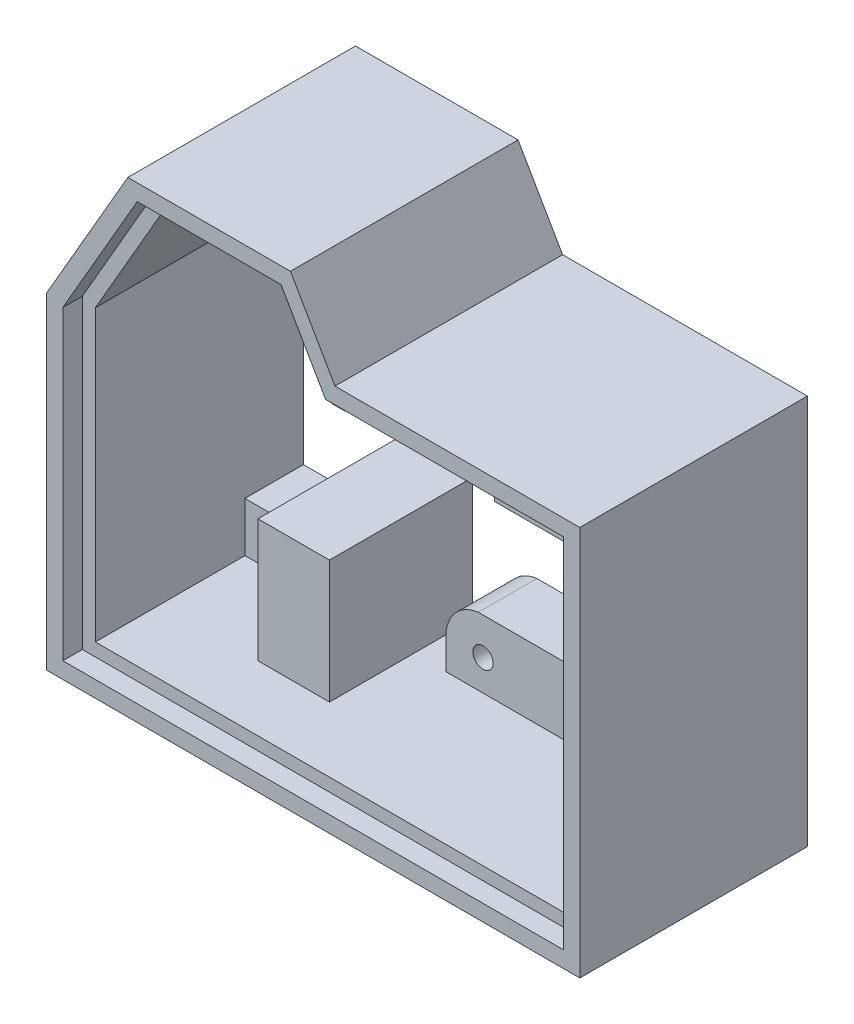
SolidWorks part; units mm, degrees
ref_plane "Front Plane" through (0, 0, 0) normal (0, 0, 1) x (1, 0, 0)
ref_plane "Top Plane" through (0, 0, 0) normal (0, 1, 0) x (1, 0, 0)
ref_plane "Right Plane" through (0, 0, 0) normal (1, 0, 0) x (0, 0, -1)
sketch "Sketch1" plane through (0, 0, 0) normal (0, 0, 1) x (1, 0, 0)
  line L1 (0, 0) -> (82, 0)
  line L2 (0, 0) -> (0, 50.2188)
  line L3 (5.6472, 60) -> (82, 60)
  line L4 (82, 0) -> (82, 60)
  line L5 (0, 50.2188) -> (50, 50.2188)
  line L6 (12.5, 71.8694) -> (12.5, 50.2188)
  line L10 (50, 50.2188) -> (37.5, 71.8694)
  line L11 (37.5, 71.8694) -> (12.5, 71.8694)
  line L12 (12.5, 71.8694) -> (0, 50.2188)
  line L13 (37.5, 28.5681) -> (43.75, 39.3934) [skipped]
  line L14 (12.5, 28.5681) -> (25, 28.5681) [skipped]
  line L15 (0, 50.2188) -> (6.25, 39.3934) [skipped]
  arc A0 (46.6506, 50.2188) -> (3.3494, 50.2188) centre (25, 50.2188) ccw construction
  dimension "D1" = 50.2188
  dimension "D4" = 21.6506
extrude "Boss-Extrude1" add sketch "Sketch1" along normal blind 35 contours L10 L11 L6 L3 | L3 L12 L5 L6 | L6 L12 L3 | L5 L10 L3 L6 | L10 L5 L2 L1 L4 L3
sketch "Sketch3" plane through (0, 0, 35) normal (0, 0, 1) x (1, 0, 0)
  line L14 (42.9094, 57.5) -> (36.0566, 69.3694)
  line L15 (36.0566, 69.3694) -> (13.9434, 69.3694)
  line L16 (13.9434, 69.3694) -> (2.5, 49.5489)
  line L17 (2.5, 49.5489) -> (2.5, 2.5)
  line L18 (2.5, 2.5) -> (79.5, 2.5)
  line L19 (79.5, 2.5) -> (79.5, 57.5)
  line L20 (79.5, 57.5) -> (42.9094, 57.5)
  line L21 (42.9094, 57.5) -> (36.0566, 69.3694)
  line L22 (36.0566, 69.3694) -> (13.9434, 69.3694)
  line L23 (13.9434, 69.3694) -> (2.5, 49.5489)
  line L24 (2.5, 49.5489) -> (2.5, 2.5)
  line L25 (2.5, 2.5) -> (79.5, 2.5)
  line L26 (79.5, 2.5) -> (79.5, 57.5)
  line L27 (79.5, 57.5) -> (42.9094, 57.5)
  point P0 (0, 0)
  dimension "D1" = 2.5
extrude "Cut-Extrude1" cut sketch "Sketch3" against normal blind 26
sketch "Sketch4" plane through (0, 0, 9) normal (0, 0, 1) x (1, 0, 0)
  line L1 (79.5, 57.5) -> (42.9094, 57.5)
  line L2 (79.5, 57.5) -> (79.5, 40.85)
  line L3 (79.5, 40.85) -> (42.9094, 40.85)
  line L4 (42.9094, 57.5) -> (42.9094, 40.85)
  dimension "D1" = 16.65
extrude "Boss-Extrude2" add sketch "Sketch4" along normal blind 4.3
sketch "Sketch5" plane through (0, 0, 13.3) normal (0, 0, 1) x (1, 0, 0)
  line L0 (79.5, 57.5) -> (42.9094, 57.5) construction
  line L1 (49.5276, 57.5) -> (72.1276, 57.5)
  line L2 (49.5276, 57.5) -> (49.5276, 45.65)
  line L3 (49.5276, 45.65) -> (72.1276, 45.65)
  line L4 (72.1276, 57.5) -> (72.1276, 45.65)
  line L5 (79.5, 40.85) -> (79.5, 57.5) construction
  dimension "D1" = 7.3724
  dimension "D2" = 22.6
  dimension "D3" = 11.85
extrude "Cut-Extrude2" cut sketch "Sketch5" against normal blind 4.2
sketch "Sketch6" plane through (0, 0, 9.1) normal (0, 0, 1) x (1, 0, 0)
  line L0 (49.5276, 57.5) -> (49.5276, 45.65) construction
  line L1 (49.5276, 45.65) -> (72.1276, 45.65) construction
  line L2 (49.5276, 51.55) -> (61.7276, 51.55)
  line L3 (61.7276, 54.15) -> (60.7239, 54.15)
  line L5 (60.7239, 48.95) -> (61.7276, 48.95)
  arc A0 (60.7239, 54.15) -> (60.7239, 48.95) centre (55.4276, 51.55) ccw
  arc A1 (61.7276, 48.95) -> (61.7276, 54.15) centre (61.7276, 51.55) ccw
  point P8 (0, 0)
  point P10 (0, 0)
  dimension "D2" = 11.8
  dimension "D5" = 5.2
  dimension "D1" = 5.9
  dimension "D3" = 5.9
  dimension "D4" = 12.2
extrude "Cut-Extrude3" cut sketch "Sketch6" against normal blind 17.2
sketch "Sketch7" plane through (0, 0, 9) normal (0, 0, 1) x (1, 0, 0)
  line L2 (40.9094, 57.5) -> (40.9094, 40.85)
  line L3 (40.9094, 56.9641) -> (40.9094, 54.4298)
  line L4 (42.9094, 54.4298) -> (42.9094, 57.5)
  line L5 (42.9094, 57.5) -> (36.0566, 69.3694)
  line L6 (36.0566, 69.3694) -> (13.9434, 69.3694)
  line L7 (13.9434, 69.3694) -> (2.5, 49.5489)
  line L8 (2.5, 49.5489) -> (2.5, 2.5)
  line L9 (2.5, 2.5) -> (79.5, 2.5) construction
  line L10 (2.5, 2.5) -> (79.5, 2.5)
  line L11 (79.5, 2.5) -> (79.5, 40.85)
  line L12 (42.9094, 40.85) -> (79.5, 40.85) construction
  line L13 (79.5, 2.5) -> (79.5, 40.85) construction
  line L14 (79.5, 40.85) -> (77.5, 40.85)
  line L15 (40.9094, 54.4298) -> (42.9094, 54.4298)
  line L28 (77.5, 4.5) -> (77.5, 40.85)
  line L29 (4.5, 4.5) -> (77.5, 4.5)
  line L30 (4.5, 49.013) -> (4.5, 4.5)
  line L31 (15.0981, 67.3694) -> (4.5, 49.013)
  line L32 (34.9019, 67.3694) -> (15.0981, 67.3694)
  line L33 (41.1774, 56.5) -> (34.9019, 67.3694)
  line L34 (77.5, 4.5) -> (77.5, 40.85)
  line L35 (4.5, 4.5) -> (77.5, 4.5)
  line L36 (4.5, 49.013) -> (4.5, 4.5)
  line L37 (15.0981, 67.3694) -> (4.5, 49.013)
  line L38 (34.9019, 67.3694) -> (15.0981, 67.3694)
  line L39 (40.9094, 56.9641) -> (34.9019, 67.3694)
  dimension "D1" = 2
  dimension "D2" = 2
extrude "Boss-Extrude3" add sketch "Sketch7" along normal blind 23
sketch "Sketch11" plane through (0, 0, 9) normal (0, 0, 1) x (1, 0, 0)
  line L0 (0, 0) -> (0, 50.2188) construction
  line L1 (0, 0) -> (82, 0) construction
  line L2 (8.89, 51.8599) -> (6.1437, 51.8599)
  line L3 (4.5, 49.013) -> (15.0981, 67.3694) construction
  line L4 (8.89, 45.3989) -> (4.5, 45.3989)
  line L5 (4.5, 4.5) -> (4.5, 49.013) construction
  line L6 (8.89, 12.1205) -> (4.5, 12.1205)
  line L7 (12.1205, 8.89) -> (12.1205, 4.5)
  line L8 (77.5, 4.5) -> (4.5, 4.5) construction
  line L9 (35.3985, 9.2373) -> (35.3985, 4.5)
  line L11 (42.9094, 40.85) -> (77.5, 40.85) construction
  line L12 (77.5, 4.5) -> (72.25, 4.5)
  line L13 (77.5, 4.5) -> (77.5, 40.85)
  line L14 (77.5, 40.85) -> (72.25, 40.85)
  line L15 (72.25, 4.5) -> (72.25, 40.85)
  line L16 (44.3405, 14.9023) -> (40.396, 14.9023)
  line L17 (72.25, 40.85) -> (42.9094, 40.85)
  line L18 (72.25, 40.85) -> (72.25, 30.9023)
  line L19 (72.25, 30.9023) -> (42.9094, 30.9023)
  line L20 (42.9094, 40.85) -> (42.9094, 30.9023)
  line L21 (72.25, 4.5) -> (44.3405, 4.5)
  line L22 (72.25, 4.5) -> (72.25, 14.9023)
  line L23 (72.25, 14.9023) -> (44.3405, 14.9023)
  circle A0 centre (8.89, 8.89) radius 1.5625
  circle A1 centre (8.89, 48.6294) radius 1.5625
  circle A2 centre (41.1081, 9.2373) radius 1.5625
  arc A3 (8.89, 45.3989) -> (8.89, 51.8599) centre (8.89, 48.6294) ccw
  arc A4 (12.1205, 8.89) -> (8.89, 12.1205) centre (8.89, 8.89) ccw
  arc A6 (40.396, 14.9023) -> (35.3985, 9.2373) centre (41.1081, 9.2373) ccw
  dimension "D3" = 3.125
  dimension "D6" = 6.461
  dimension "D1" = 8.89
  dimension "D2" = 8.89
  dimension "D4" = 48.6294
  dimension "D5" = 32.22
  dimension "D7" = 5.25
  dimension "D8" = 9.9477
  dimension "D9" = 16
extrude "Cut-Extrude7" cut sketch "Sketch11" against normal blind 12.54
sketch "Sketch13" plane through (0, 0, 9) normal (0, 0, 1) x (1, 0, 0)
  line L0 (77.5, 40.85) -> (77.5, 4.5) construction
  line L1 (77.5, 4.5) -> (35.3985, 4.5) construction
  line L2 (77.5, 4.5) -> (4.5, 4.5) construction
  circle A0 centre (60.0082, 11) radius 1.7526
  circle A1 centre (60.0082, 35) radius 1.7526
  dimension "D4" = 3.5052
  dimension "D1" = 17.4918
  dimension "D2" = 30.5
  dimension "D3" = 6.5
extrude "Cut-Extrude8" cut sketch "Sketch13" against normal blind 16
sketch "Sketch15" plane through (0, 0, 0) normal (0, 0, -1) x (-1, 0, 0)
  line L0 (-12.1205, 4.5) -> (-35.3985, 4.5) construction
  line L1 (-30.5, 4.5) -> (-19.5, 4.5)
  line L2 (-30.5, 4.5) -> (-30.5, 23.41)
  line L3 (-30.5, 23.41) -> (-19.5, 23.41)
  line L4 (-19.5, 4.5) -> (-19.5, 23.41)
  line L5 (0, 0) -> (0, 50.2188) construction
  line L6 (0, 0) -> (-82, 0) construction
  point P6 (-25, 23.41)
  point P9 (0, 25.1094)
  dimension "D1" = 25
  dimension "D2" = 11
  dimension "D3" = 23.41
extrude "Boss-Extrude4" add sketch "Sketch15" against normal blind 22
